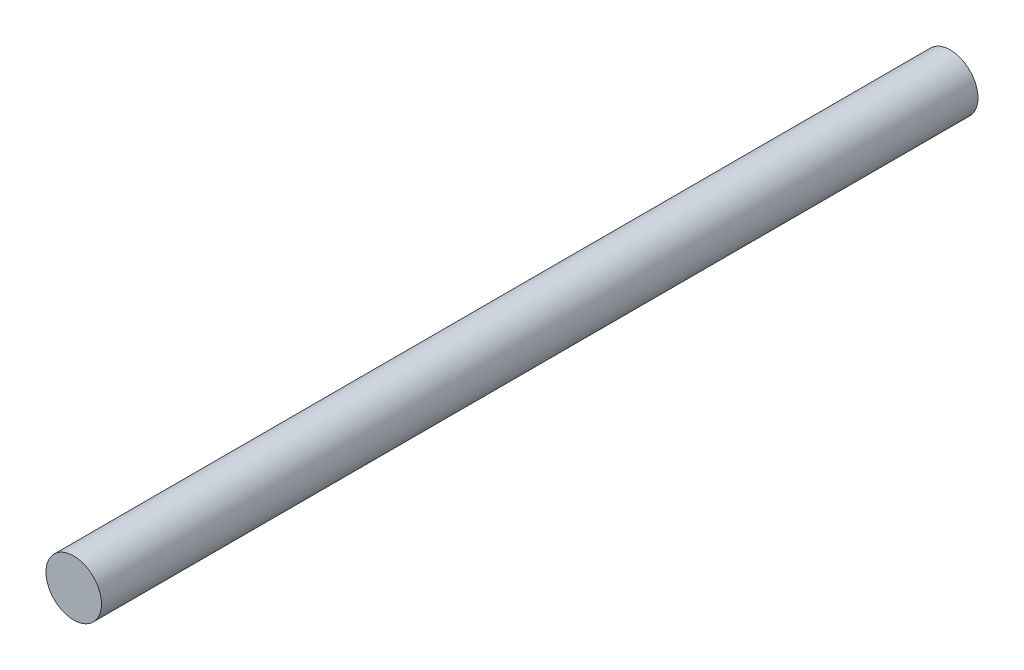
SolidWorks part; units mm, degrees
material "AISI 1020 Steel, Cold Rolled"
ref_plane "Front Plane" through (0, 0, 0) normal (0, 0, 1) x (1, 0, 0)
ref_plane "Top Plane" through (0, 0, 0) normal (0, 1, 0) x (1, 0, 0)
ref_plane "Right Plane" through (0, 0, 0) normal (1, 0, 0) x (0, 0, -1)
sketch "Sketch1" plane through (0, 0, 0) normal (0, 0, 1) x (1, 0, 0)
  circle A0 centre (0, 0) radius 2.375
  dimension "D1" = 4.75
extrude "Boss-Extrude1" add sketch "Sketch1" along normal blind 75
